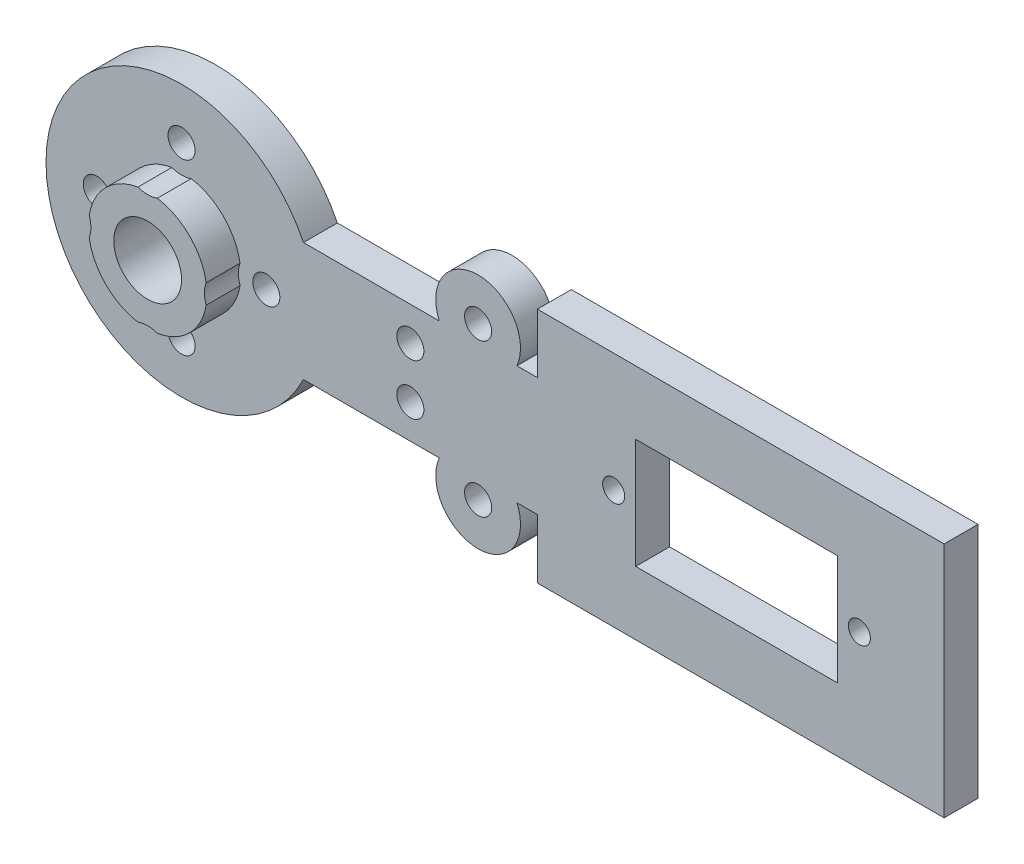
SolidWorks part; units mm, degrees
ref_plane "Front Plane" through (0, 0, 0) normal (0, 0, 1) x (1, 0, 0)
ref_plane "Top Plane" through (0, 0, 0) normal (0, 1, 0) x (1, 0, 0)
ref_plane "Right Plane" through (0, 0, 0) normal (1, 0, 0) x (0, 0, -1)
sketch "Main_web_profile" plane through (0, 0, 0) normal (0, 0, 1) x (1, 0, 0)
  line L1 (0, -7) -> (60, -7)
  line L2 (0, -7) -> (0, 7)
  line L3 (0, 7) -> (60, 7)
  line L4 (60, -7) -> (60, 7)
  dimension "D1" = 60
  dimension "D2" = 14
  dimension "D3" = 7
extrude "Main_web" add sketch "Main_web_profile" along normal blind 4
sketch "Shoulder_horn_flange_profile" plane through (0, 0, 0) normal (0, 0, 1) x (1, 0, 0)
  circle A0 centre (0, 0) radius 16
  dimension "D1" = 32
extrude "Shoulder_horn_flange" add sketch "Shoulder_horn_flange_profile" along normal blind 4
sketch "Elbow_servo_mount_profile" plane through (0, 0, 0) normal (0, 0, 1) x (1, 0, 0)
  line L1 (42, -14) -> (90, -14)
  line L2 (42, -14) -> (42, 14)
  line L3 (42, 14) -> (90, 14)
  line L4 (90, -14) -> (90, 14)
  dimension "D1" = 48
  dimension "D2" = 28
  dimension "D3" = 42
  dimension "D4" = 14
extrude "Elbow_servo_mount" add sketch "Elbow_servo_mount_profile" along normal blind 4
sketch "SG90_body_clearance_profile" plane through (0, 0, 0) normal (0, 0, 1) x (1, 0, 0)
  line L1 (53.6, -6.5) -> (77.4, -6.5)
  line L2 (53.6, -6.5) -> (53.6, 6.5)
  line L3 (53.6, 6.5) -> (77.4, 6.5)
  line L4 (77.4, -6.5) -> (77.4, 6.5)
  dimension "D1" = 23.8
  dimension "D2" = 13
  dimension "D3" = 53.6
  dimension "D4" = 6.5
extrude "SG90_body_clearance" cut sketch "SG90_body_clearance_profile" along normal through all from offset 5
sketch "Elbow_tab_fasteners_profile" plane through (0, 0, 0) normal (0, 0, 1) x (1, 0, 0)
  circle A0 centre (51, 0) radius 1.3
  circle A1 centre (80, 0) radius 1.3
  dimension "D1" = 2.6
  dimension "D2" = 2.6
  dimension "D3" = 51
  dimension "D4" = 80
extrude "Elbow_tab_fasteners" cut sketch "Elbow_tab_fasteners_profile" along normal through all from offset 50
sketch "Shoulder_center_screw_access_profile" plane through (0, 0, 0) normal (0, 0, 1) x (1, 0, 0)
  circle A0 centre (0, 0) radius 4
  dimension "D1" = 8
extrude "Shoulder_center_screw_access" cut sketch "Shoulder_center_screw_access_profile" along normal through all from offset 50
sketch "Shoulder_horn_bolt_pattern_profile" plane through (0, 0, 0) normal (0, 0, 1) x (1, 0, 0)
  circle A0 centre (0, 10) radius 1.6
  circle A1 centre (0, -10) radius 1.6
  circle A2 centre (10, 0) radius 1.6
  circle A3 centre (-10, 0) radius 1.6
  dimension "D1" = 3.2
  dimension "D2" = 3.2
  dimension "D3" = 3.2
  dimension "D4" = 3.2
  dimension "D5" = 10
  dimension "D6" = 10
  dimension "D7" = 10
  dimension "D8" = 10
extrude "Shoulder_horn_bolt_pattern" cut sketch "Shoulder_horn_bolt_pattern_profile" along normal through all from offset 50
sketch "Cable_tie_holes_profile" plane through (0, 0, 0) normal (0, 0, 1) x (1, 0, 0)
  circle A0 centre (27, -3) radius 1.6
  circle A1 centre (27, 3) radius 1.6
  dimension "D1" = 3.2
  dimension "D2" = 3.2
  dimension "D3" = 27
  dimension "D4" = 3
  dimension "D5" = 3
extrude "Cable_tie_holes" cut sketch "Cable_tie_holes_profile" along normal through all from offset 50
sketch "Passive_lower_mount_boss_profile" plane through (0, 0, 0) normal (0, 0, 1) x (1, 0, 0)
  circle A0 centre (35, -9) radius 5
  dimension "D1" = 10
  dimension "D2" = 35
  dimension "D3" = 9
extrude "Passive_lower_mount_boss" add sketch "Passive_lower_mount_boss_profile" along normal blind 4
sketch "Passive_upper_mount_boss_profile" plane through (0, 0, 0) normal (0, 0, 1) x (1, 0, 0)
  circle A0 centre (35, 9) radius 5
  dimension "D1" = 10
  dimension "D2" = 35
  dimension "D3" = 9
extrude "Passive_upper_mount_boss" add sketch "Passive_upper_mount_boss_profile" along normal blind 4
sketch "Passive_cheek_standoffs_profile" plane through (0, 0, 0) normal (0, 0, 1) x (1, 0, 0)
  circle A0 centre (35, -9) radius 1.6
  circle A1 centre (35, 9) radius 1.6
  dimension "D1" = 3.2
  dimension "D2" = 3.2
  dimension "D3" = 35
  dimension "D4" = 9
  dimension "D5" = 9
extrude "Passive_cheek_standoffs" cut sketch "Passive_cheek_standoffs_profile" along normal through all from offset 50
sketch "Shoulder_dowel_support_hub_profile" plane through (0, 0, 0) normal (0, 0, 1) x (1, 0, 0)
  circle A0 centre (0, 0) radius 7
  circle A1 centre (0, 0) radius 4
  dimension "D1" = 14
  dimension "D2" = 8
extrude "Shoulder_dowel_support_hub" add sketch "Shoulder_dowel_support_hub_profile" along normal blind 4 from offset 4
sketch "Shoulder_horn_washer_hub_relief_profile" plane through (0, 0, 0) normal (0, 0, 1) x (1, 0, 0)
  circle A0 centre (10, 0) radius 3.3
  circle A1 centre (-10, 0) radius 3.3
  circle A2 centre (0, 10) radius 3.3
  circle A3 centre (0, -10) radius 3.3
  dimension "D1" = 6.6
  dimension "D2" = 6.6
  dimension "D3" = 6.6
  dimension "D4" = 6.6
  dimension "D5" = 10
  dimension "D6" = 10
  dimension "D7" = 10
  dimension "D8" = 10
extrude "Shoulder_horn_washer_hub_relief" cut sketch "Shoulder_horn_washer_hub_relief_profile" along normal blind 4 from offset 4
